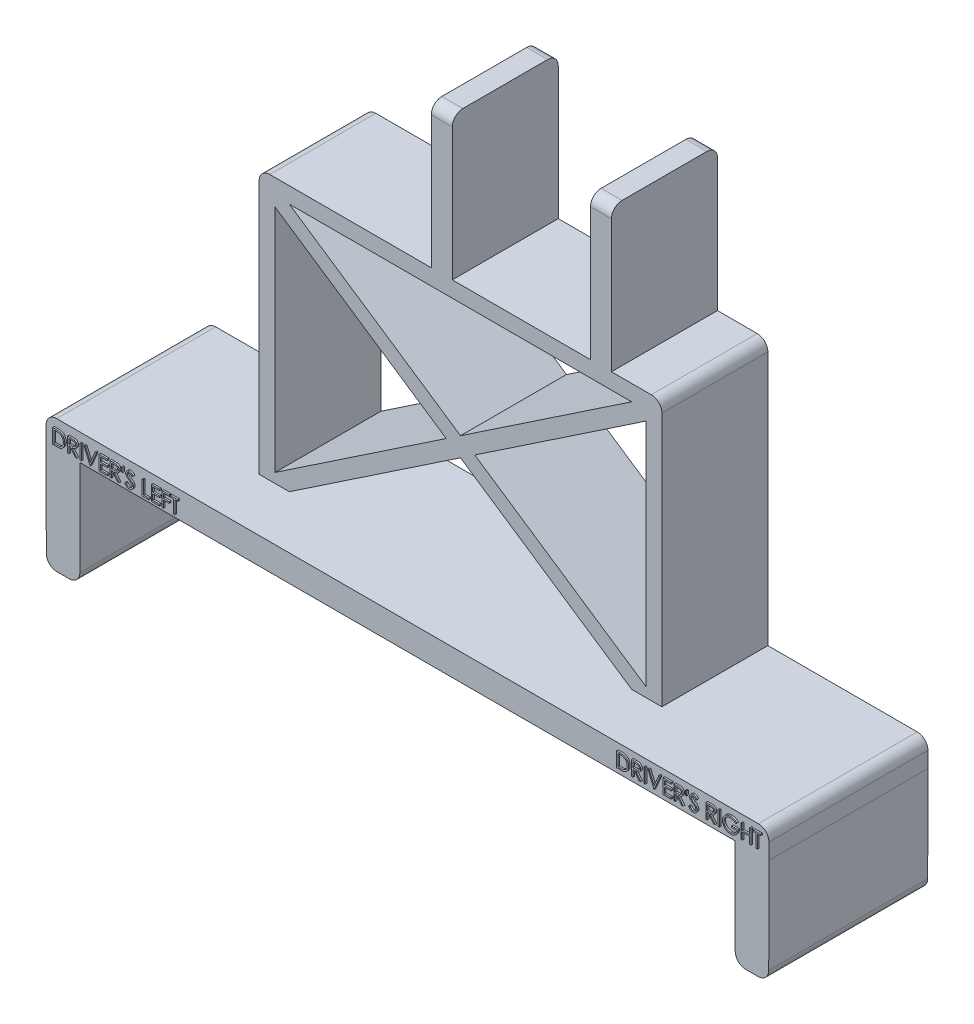
SolidWorks part; units mm, degrees
ref_plane "Front Plane" through (0, 0, 0) normal (0, 0, 1) x (1, 0, 0)
ref_plane "Top Plane" through (0, 0, 0) normal (0, 1, 0) x (1, 0, 0)
ref_plane "Right Plane" through (0, 0, 0) normal (1, 0, 0) x (0, 0, -1)
sketch "Sketch1" plane through (0, 0, 0) normal (0, 0, 1) x (1, 0, 0)
  line L12 (8.128, 0) -> (8.128, 25.4)
  line L13 (8.128, 0) -> (0, 0)
  line L24 (165.1, 0) -> (165.1, 25.4)
  line L30 (0, 31.75) -> (173.228, 31.75)
  line L32 (8.128, 25.4) -> (165.1, 25.4)
  line L33 (173.228, 31.75) -> (173.228, 0)
  line L34 (0, 31.75) -> (0, 1041.4108) construction
  line L37 (165.1, 0) -> (173.228, 0)
  line L38 (0, 31.75) -> (0, 0)
  point P1 (4.064, 45.8515)
  point P2 (0, 0)
  point P3 (0, 0)
  point P4 (0, 0)
  dimension "D2" = 8.128
  dimension "D3" = 173.228
  dimension "D4" = 25.4
  dimension "D5" = 8.128
  dimension "D12" = 6.35
extrude "Boss-Extrude2" add sketch "Sketch1" along normal blind 38.1
sketch "Sketch7" plane through (0, 0, 0) normal (0, 0, 1) x (1, 0, 0)
  line L0 (86.614, 68.2701) -> (86.614, 42.7511) construction
  line L2 (173.228, 31.75) -> (0, 31.75) construction
  line L3 (173.228, 31.75) -> (0, 31.75) construction
  line L6 (38.354, 95.25) -> (38.354, 31.75)
  line L7 (38.354, 31.75) -> (42.164, 31.75)
  line L8 (134.874, 95.25) -> (134.874, 31.75)
  line L9 (38.354, 95.25) -> (134.874, 95.25)
  line L13 (42.164, 31.75) -> (42.164, 91.44)
  line L14 (131.064, 91.44) -> (131.064, 31.75)
  line L15 (42.164, 91.44) -> (131.064, 91.44)
  line L16 (131.064, 31.75) -> (134.874, 31.75)
  point P4 (86.614, 31.75)
  point P6 (0, 0)
  point P7 (134.874, 104.14)
  point P11 (131.064, 115.2427)
  point P14 (134.874, 104.14)
  point P15 (86.614, 95.25)
  point P18 (38.354, 102.2386)
  point P21 (134.874, 104.14)
  dimension "D2" = 3.81
  dimension "D3" = 63.5
  dimension "D4" = 44.45
  dimension "D5" = 3.81
extrude "Boss-Extrude6" add sketch "Sketch7" along normal blind 25.4
sketch "Sketch6" plane through (0, 95.25, 0) normal (0, 1, 0) x (1, 0, 0)
  line L26 (134.874, 0) -> (38.354, 0) construction
  line L30 (79.6112, 0) -> (79.6112, -25.4)
  line L31 (79.6112, -25.4) -> (84.6912, -25.4)
  line L32 (84.6912, 0) -> (84.6912, -25.4)
  line L33 (79.6112, 0) -> (84.6912, 0)
  line L34 (117.7112, 0) -> (117.7112, -25.4)
  line L35 (117.7112, -25.4) -> (122.7912, -25.4)
  line L36 (122.7912, 0) -> (122.7912, -25.4)
  line L37 (117.7112, 0) -> (122.7912, 0)
  line L46 (134.874, -25.4) -> (38.354, -25.4) construction
  line L51 (0, -38.1) -> (0, 0) construction
  point P32 (117.7112, -12.7)
  dimension "D2" = 84.6912
  dimension "D5" = 5.08
  dimension "D6" = 5.08
  dimension "D15" = 33.02
extrude "Boss-Extrude5" add sketch "Sketch6" along normal blind 34.29
fillet "Fillet1" radius 2.54 8 edges at (120.2512, 129.54, 0) (82.1512, 129.54, 0) (120.2512, 129.54, 25.4) (82.1512, 129.54, 25.4) (173.228, 31.75, 19.05) (134.874, 95.25, 12.7) (0, 31.75, 19.05) (38.354, 95.25, 12.7)
sketch "Sketch11" plane through (0, 0, 0) normal (0, 0, 1) x (1, 0, 0)
  line L0 (42.164, 89.1454) -> (83.1966, 61.595)
  line L3 (127.6466, 31.75) -> (131.064, 31.75)
  line L4 (131.064, 31.75) -> (131.064, 34.0446)
  line L5 (131.064, 91.44) -> (131.064, 31.75) construction
  line L6 (131.064, 34.0446) -> (90.0314, 61.595)
  line L8 (45.5814, 91.44) -> (42.164, 91.44)
  line L9 (42.164, 91.44) -> (42.164, 89.1454)
  line L10 (127.6466, 91.44) -> (131.064, 91.44)
  line L11 (131.064, 91.44) -> (131.064, 89.1454)
  line L12 (131.064, 89.1454) -> (90.0314, 61.595)
  line L13 (45.5814, 31.75) -> (42.164, 31.75)
  line L14 (42.164, 31.75) -> (42.164, 34.0446)
  line L15 (42.164, 34.0446) -> (83.1966, 61.595)
  line L16 (42.164, 31.75) -> (131.064, 91.44) construction
  line L17 (42.164, 91.44) -> (131.064, 31.75) construction
  line L18 (86.614, 59.3004) -> (45.5814, 31.75)
  line L19 (86.614, 59.3004) -> (127.6466, 31.75)
  line L20 (86.614, 63.8896) -> (127.6466, 91.44)
  line L21 (86.614, 63.8896) -> (45.5814, 91.44)
  line L23 (42.164, 31.75) -> (42.164, 91.44) construction
  line L24 (42.164, 91.44) -> (131.064, 91.44) construction
  line L25 (170.688, 31.75) -> (2.54, 31.75) construction
  point P2 (45.3362, 31.75)
  point P3 (42.164, 31.75)
  point P4 (131.064, 31.75)
  point P11 (0, 0)
  point P12 (131.064, 100.33)
  point P18 (0, 0)
  point P23 (42.164, 100.33)
  point P34 (42.164, 97.924)
  point P35 (0, 0)
  point P36 (0, 0)
  point P37 (0, 0)
  point P39 (131.064, 31.75)
  dimension "D1" = 3.81
  dimension "D2" = 3.81
extrude "Boss-Extrude7" add sketch "Sketch11" along normal up to surface (25.4 mm away) up to face at (93.0972, 87.5473, 25.4)
sketch "Sketch3" plane through (0, 0, 38.1) normal (0, 0, 1) x (1, 0, 0)
  line L2 (79.6112, 129.54) -> (84.6912, 129.54) construction
  line L8 (84.6912, 95.25) -> (84.6404, 95.25)
  line L9 (84.6912, 95.25) -> (84.6912, 129.54)
  line L10 (84.6912, 129.54) -> (84.6404, 129.54)
  line L11 (84.6404, 95.25) -> (84.6404, 129.54)
  line L12 (117.7112, 95.25) -> (117.762, 95.25)
  line L13 (117.7112, 95.25) -> (117.7112, 129.54)
  line L14 (117.7112, 129.54) -> (117.762, 129.54)
  line L15 (117.762, 95.25) -> (117.762, 129.54)
  line L41 (0, 25.4) -> (0.0508, 0)
  line L45 (0, 29.21) -> (0, 0) construction
  line L48 (0, 0) -> (8.128, 0) construction
  line L49 (0.0508, 0) -> (0, 0)
  line L50 (0, 0) -> (0, 25.4)
  line L51 (8.128, 25.4) -> (8.0772, 0)
  line L52 (8.0772, 0) -> (8.128, 0)
  line L53 (165.1, 0) -> (165.1, 25.4)
  line L54 (165.1, 25.4) -> (165.1508, 0)
  line L58 (165.1, 0) -> (173.228, 0) construction
  line L59 (165.1508, 0) -> (165.1, 0)
  line L91 (173.228, 25.4) -> (173.1772, 0)
  line L95 (173.228, 0) -> (173.228, 29.21) construction
  line L97 (173.1772, 0) -> (173.228, 0)
  line L99 (173.228, 0) -> (173.228, 25.4)
  line L101 (8.128, 25.4) -> (165.1, 25.4) construction
  line L129 (117.7112, 129.54) -> (122.7912, 129.54) construction
  line L130 (8.128, 25.4) -> (8.128, 0)
  point P29 (8.3812, 25.4)
  dimension "D3" = 0.0508
  dimension "D2" = 0.0508
  dimension "D4" = 0.0508
  dimension "D5" = 0.0508
  dimension "D6" = 0.0508
  dimension "D1" = 0.0508
extrude "Clearance Trim" cut sketch "Sketch3" against normal up to surface (38.1 mm away)
fillet "Fillet2" radius 2.54 4 edges at (165.1508, 0, 19.05) (173.1772, 0, 19.05) (8.0772, 0, 19.05) (0.0508, 0, 19.05)
sketch "Sketch12" plane through (0, 0, 38.1) normal (0, 0, 1) x (1, 0, 0)
  text T0 "DRIVER'S RIGHT"
  text T1 "DRIVER'S LEFT\r\n"
extrude "Text" add sketch "Sketch12" along normal blind 0.4
